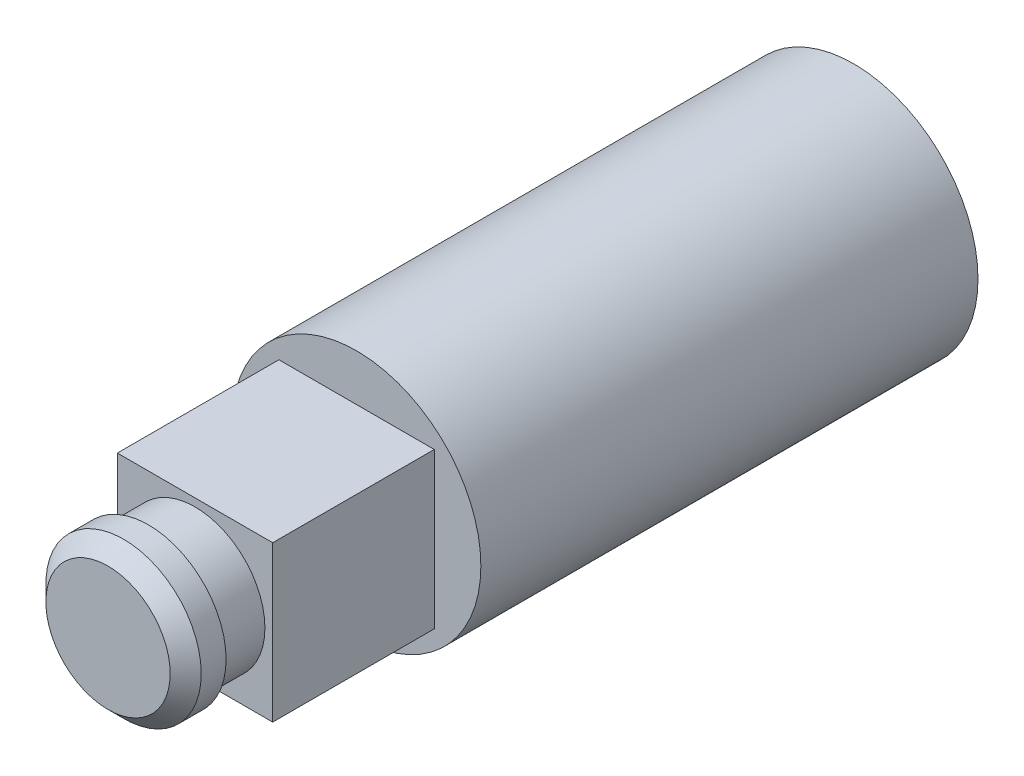
SolidWorks part; units mm, degrees
ref_plane "前视基准面" through (0, 0, 0) normal (0, 0, 1) x (1, 0, 0)
ref_plane "上视基准面" through (0, 0, 0) normal (0, 1, 0) x (1, 0, 0)
ref_plane "右视基准面" through (0, 0, 0) normal (1, 0, 0) x (0, 0, -1)
sketch "草图1" plane through (0, 0, 0) normal (0, 0, 1) x (1, 0, 0)
  circle A0 centre (0, 0) radius 4
  dimension "D1" = 8
extrude "凸台-拉伸1" add sketch "草图1" along normal mid plane 16
sketch "草图2" plane through (0, 0, 8) normal (0, 0, 1) x (1, 0, 0)
  line L1 (-2.5, -2.5) -> (2.5, -2.5)
  line L2 (-2.5, -2.5) -> (-2.5, 2.5)
  line L3 (-2.5, 2.5) -> (2.5, 2.5)
  line L4 (2.5, -2.5) -> (2.5, 2.5)
  line L5 (-2.5, -2.5) -> (2.5, 2.5) construction
  line L6 (-2.5, 2.5) -> (2.5, -2.5) construction
  point P0 (0, 0)
  dimension "D1" = 5
extrude "凸台-拉伸2" add sketch "草图2" along normal blind 5.2
sketch "草图3" plane through (0, 0, 13.2) normal (0, 0, 1) x (1, 0, 0)
  circle A0 centre (0, 0) radius 2.5
extrude "凸台-拉伸3" add sketch "草图3" along normal offset from surface (2.8 mm away) 24 up to face at (4, 0, -8)
sketch "草图4" plane through (0, 0, 13.2) normal (0, 0, 1) x (1, 0, 0)
  circle A0 centre (0, 0) radius 2.25
  dimension "D1" = 4.5
extrude "切除-拉伸1" cut sketch "草图4" along normal blind 1.5 flip side to cut
chamfer "倒角1" distance 0.5 angle 45 1 edges at (2.5, 0, 16)
equation "\"1W6\"=10"
